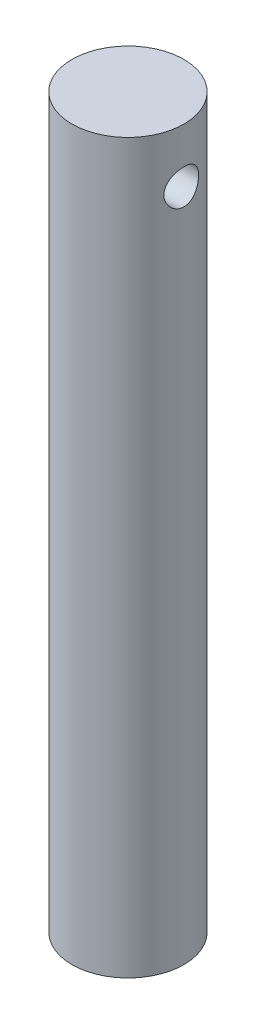
SolidWorks part; units mm, degrees
ref_plane "前视基准面" through (0, 0, 0) normal (0, 0, 1) x (1, 0, 0)
ref_plane "上视基准面" through (0, 0, 0) normal (0, 1, 0) x (1, 0, 0)
ref_plane "右视基准面" through (0, 0, 0) normal (1, 0, 0) x (0, 0, -1)
sketch "草图1" plane through (0, 0, 0) normal (0, 1, 0) x (1, 0, 0)
  circle A0 centre (0, 0) radius 10
  dimension "D1" = 20
extrude "凸台-拉伸1" add sketch "草图1" along normal blind 130
sketch "草图2" plane through (0, 130, 0) normal (0, 1, 0) x (1, 0, 0)
  line L0 (0, 0) -> (10, 0)
  circle A0 centre (0, 0) radius 10 construction
hole_wizard "Ø6.2 (6.2) 直径孔1" positions "3D草图1" profile "草图3" hole size "Ø6.2" standard "GB" end condition through all
sketch3d "3D草图1"
  line L1 (10, 130, 0) -> (10, 120.3, 0) construction
  point P0 (10, 120.3, 0)
  dimension "D1" = 9.7
sketch "草图3" plane through (10, 120.3, 0) normal (0, 1, 0) x (0, 0, -1)
  line L0 (0, 0) -> (0, 20)
  line L1 (0, 20) -> (3.1, 20)
  line L2 (3.1, 20) -> (3.1, 0)
  line L5 (3.1, 0) -> (0, 0)
  line L11 (0, -6.35) -> (0, 107.95) construction
  dimension "通孔孔直径" = 6.2
  dimension "通孔孔深度" = 20
